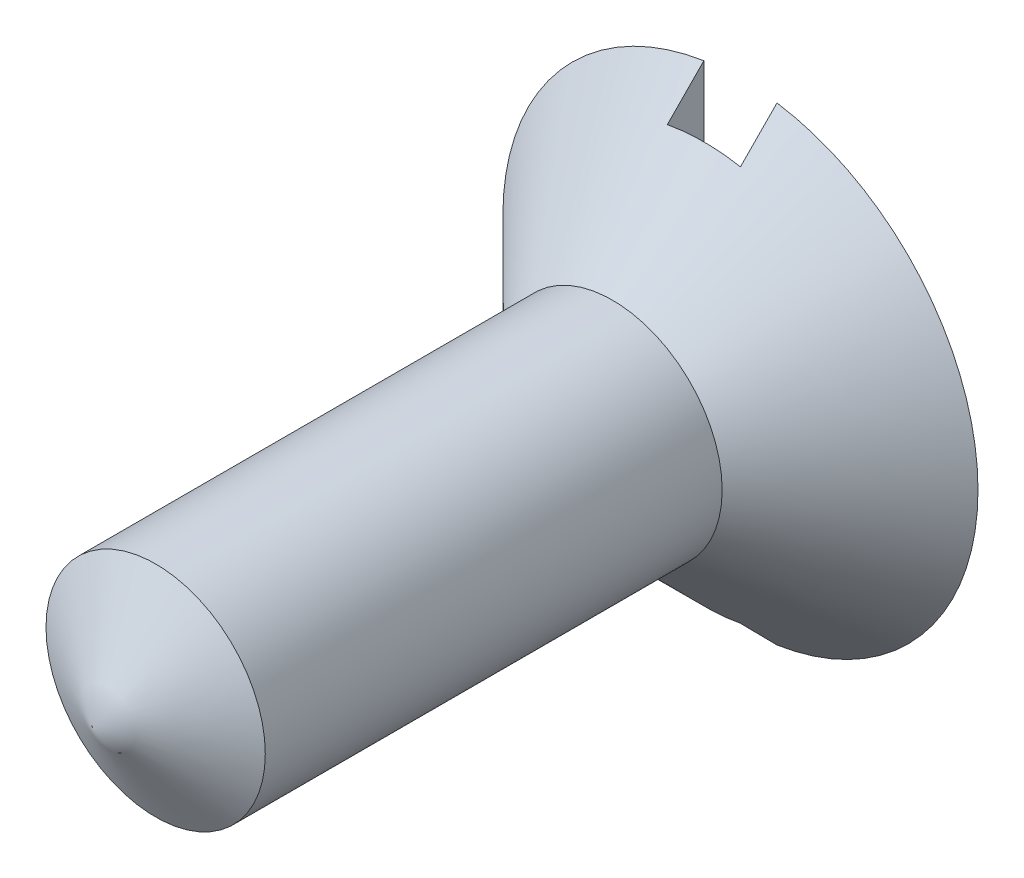
SolidWorks part; units mm, degrees
ref_plane "Front Plane" through (0, 0, 0) normal (0, 0, 1) x (1, 0, 0)
ref_plane "Top Plane" through (0, 0, 0) normal (0, 1, 0) x (1, 0, 0)
ref_plane "Right Plane" through (0, 0, 0) normal (1, 0, 0) x (0, 0, -1)
sketch "Sketch1" plane through (0, 0, 0) normal (0, 1, 0) x (1, 0, 0)
  line L0 (9.6972, 48.221) -> (6.1972, 44.721)
  line L1 (3.1972, 48.221) -> (9.6972, 48.221)
  line L2 (6.1972, 44.721) -> (6.1972, 32.221)
  line L3 (6.1972, 32.221) -> (3.1972, 30.489)
  line L4 (3.1972, 48.221) -> (3.1972, 30.489)
  dimension "D1" = 6.5
  dimension "D2" = 45
  dimension "D3" = 12.5
  dimension "D4" = 3
  dimension "D5" = 120
revolve "Revolve1" add sketch "Sketch1" angle 360 about L4
sketch "Sketch2" plane through (0, 0, 0) normal (0, 1, 0) x (1, 0, 0)
  line L0 (9.6972, 48.221) -> (-3.3028, 48.221) construction
  line L1 (2.1972, 48.221) -> (4.1972, 48.221)
  line L2 (2.1972, 48.221) -> (2.1972, 47.221)
  line L3 (2.1972, 47.221) -> (4.1972, 47.221)
  line L4 (4.1972, 48.221) -> (4.1972, 47.221)
  dimension "D1" = 5.5
  dimension "D2" = 5.5
  dimension "D3" = 1
extrude "Cut-Extrude1" cut sketch "Sketch2" against normal blind 12 and the other way through all
sketch "Sketch3" plane through (0, 0, 0) normal (0, 1, 0) x (1, 0, 0)
equation "\"2mmmm\"=1.36747"
